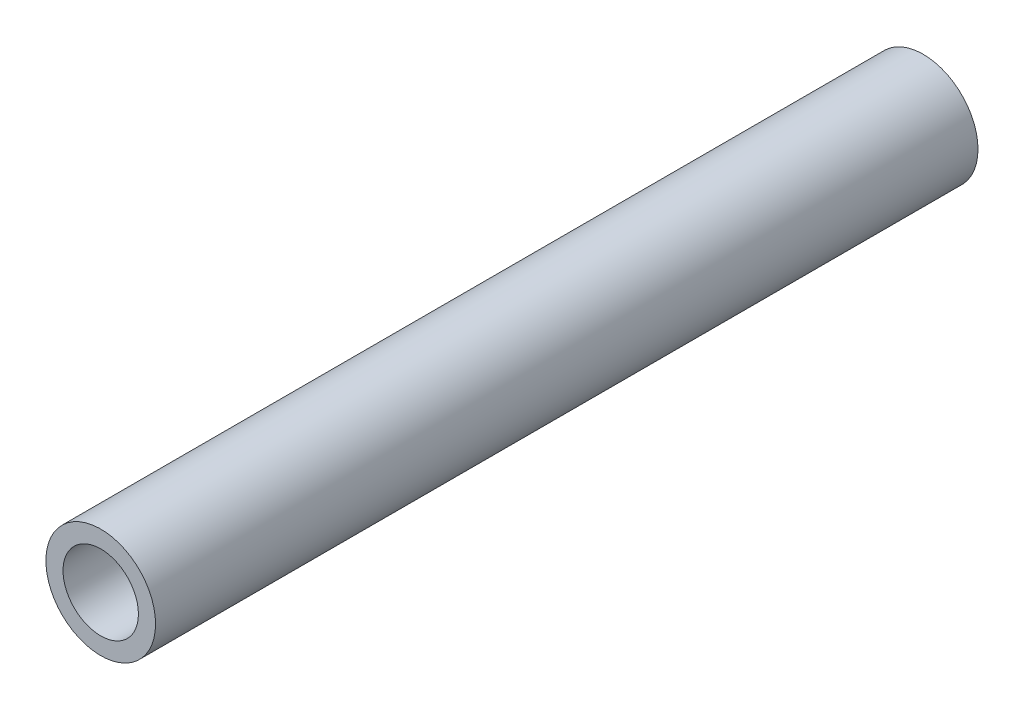
SolidWorks part; units mm, degrees
ref_plane "Front Plane" through (0, 0, 0) normal (0, 0, 1) x (1, 0, 0)
ref_plane "Top Plane" through (0, 0, 0) normal (0, 1, 0) x (1, 0, 0)
ref_plane "Right Plane" through (0, 0, 0) normal (1, 0, 0) x (0, 0, -1)
sketch "Sketch1" plane through (0, 0, 0) normal (0, 0, 1) x (1, 0, 0)
  circle A0 centre (0, 0) radius 4
  dimension "D1" = 8
extrude "Boss-Extrude1" add sketch "Sketch1" along normal blind 60
hole_wizard "M5 Clearance Hole2" positions "Sketch4" profile "Sketch5" hole size "M5" standard "ANSI Metric" end condition through all
sketch "Sketch4" plane through (0, 0, 60) normal (0, 0, 1) x (1, 0, 0)
  point P0 (0, 0)
sketch "Sketch5" plane through (0, 0, 60) normal (1, 0, 0) x (0, -1, 0)
  line L0 (0, 0) -> (0, 60)
  line L1 (0, 60) -> (2.75, 60)
  line L2 (2.75, 60) -> (2.75, 0)
  line L5 (2.75, 0) -> (0, 0)
  line L11 (0, -6.35) -> (0, 107.95) construction
  dimension "Thru Hole Dia." = 5.5
  dimension "Thru Hole Depth" = 60
